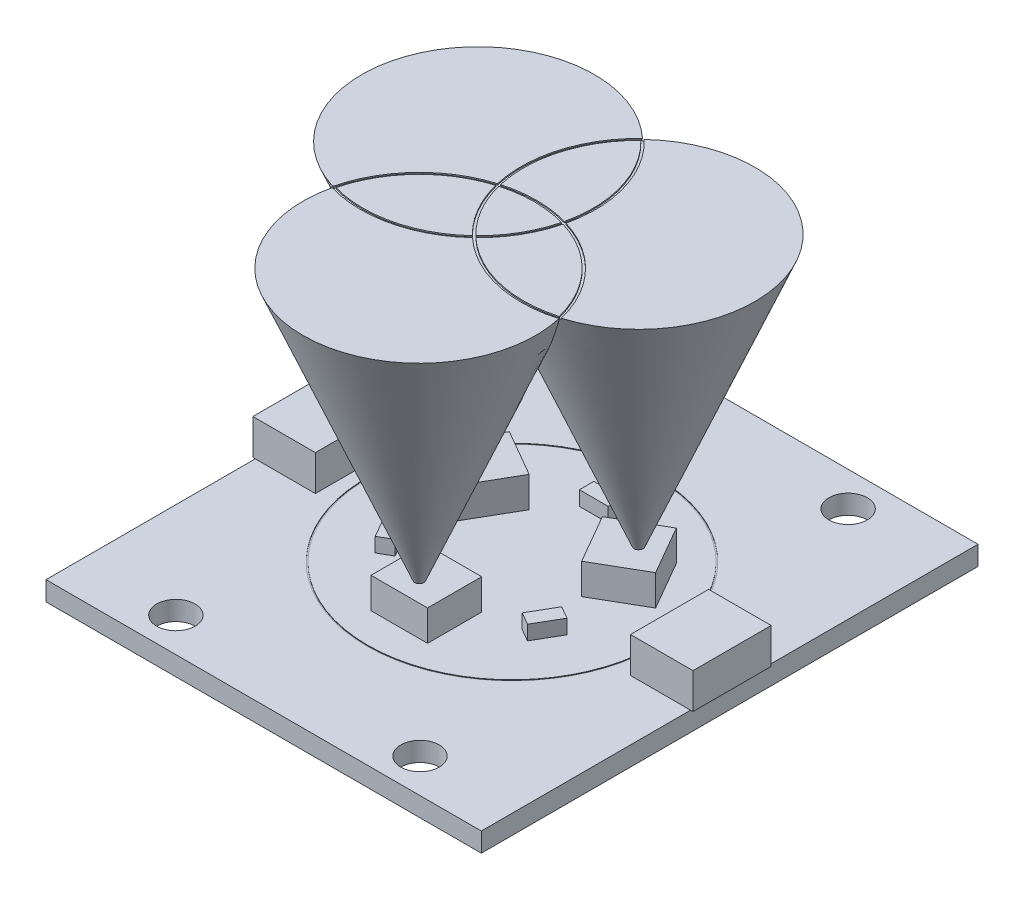
SolidWorks part; units mm, degrees
ref_plane "Front Plane" through (0, 0, 0) normal (0, 0, 1) x (1, 0, 0)
ref_plane "Top Plane" through (0, 0, 0) normal (0, 1, 0) x (1, 0, 0)
ref_plane "Right Plane" through (0, 0, 0) normal (1, 0, 0) x (0, 0, -1)
sketch "Sketch1" plane through (0, 0, 0) normal (0, 1, 0) x (1, 0, 0)
  line L1 (-18.1, -20.65) -> (18.1, -20.65)
  line L2 (-18.1, -20.65) -> (-18.1, 20.65)
  line L3 (-18.1, 20.65) -> (18.1, 20.65)
  line L4 (18.1, -20.65) -> (18.1, 20.65)
  line L5 (-18.1, -20.65) -> (18.1, 20.65) construction
  line L6 (-18.1, 20.65) -> (18.1, -20.65) construction
  line L7 (10.15, -17.8) -> (-10.15, -17.8) construction
  line L8 (10.15, -17.8) -> (10.15, 17.8) construction
  line L9 (10.15, 17.8) -> (-10.15, 17.8) construction
  line L10 (-10.15, -17.8) -> (-10.15, 17.8) construction
  line L11 (10.15, -17.8) -> (-10.15, 17.8) construction
  line L12 (10.15, 17.8) -> (-10.15, -17.8) construction
  circle A0 centre (-10.15, 17.8) radius 1.6
  circle A1 centre (10.15, 17.8) radius 1.6
  circle A2 centre (-10.15, -17.8) radius 1.6
  circle A3 centre (10.15, -17.8) radius 1.6
  point P0 (0, 0)
  point P6 (0, 0)
  dimension "D3" = 3.2
  dimension "D1" = 36.2
  dimension "D2" = 41.3
  dimension "D4" = 20.3
  dimension "D5" = 35.6
extrude "Boss-Extrude1" add sketch "Sketch1" along normal blind 1.6
sketch "Sketch2" plane through (0, 1.6, 0) normal (0, 1, 0) x (1, 0, 0)
  line L0 (-18.1, 0) -> (18.1, 0) construction
  line L2 (18.1, -20.65) -> (18.1, 20.65) construction
  line L3 (-18.1, 20.65) -> (-18.1, -20.65) construction
  line L4 (-18.3, 3.25) -> (-13.1, 3.25)
  line L5 (-18.3, 3.25) -> (-18.3, -3.25)
  line L6 (-18.3, -3.25) -> (-13.1, -3.25)
  line L7 (-13.1, 3.25) -> (-13.1, -3.25)
  line L8 (18.3, 3.25) -> (13.1, 3.25)
  line L9 (18.3, 3.25) -> (18.3, -3.25)
  line L10 (18.3, -3.25) -> (13.1, -3.25)
  line L11 (13.1, 3.25) -> (13.1, -3.25)
  point P14 (13.1, 0)
  point P15 (-13.1, 0)
  dimension "D1" = 6.5
  dimension "D2" = 5.2
  dimension "D3" = 0.2
  dimension "D4" = 0.2
extrude "Boss-Extrude2" add sketch "Sketch2" along normal blind 2.95
sketch "Sketch3" plane through (0, 1.6, 0) normal (0, 1, 0) x (1, 0, 0)
  line L0 (-6.9417, 6.7213) -> (-3.0446, 4.4713)
  line L1 (-6.9417, 6.7213) -> (-9.2917, 2.651)
  line L2 (-3.0446, 4.4713) -> (-5.3946, 0.401)
  line L3 (-9.2917, 2.651) -> (-5.3946, 0.401)
  line L4 (3.0446, 4.4713) -> (6.9417, 6.7213)
  line L5 (3.0446, 4.4713) -> (5.3946, 0.401)
  line L6 (6.9417, 6.7213) -> (9.2917, 2.651)
  line L7 (5.3946, 0.401) -> (9.2917, 2.651)
  line L8 (-2.35, -4.8723) -> (2.35, -4.8723)
  line L9 (-2.35, -4.8723) -> (-2.35, -9.3723)
  line L10 (2.35, -4.8723) -> (2.35, -9.3723)
  line L11 (-2.35, -9.3723) -> (2.35, -9.3723)
  line L12 (0, 0) -> (-6.4952, 3.75) construction
  line L13 (0, 0) -> (6.4952, 3.75) construction
  line L14 (0, 0) -> (0, -7.5) construction
  circle A0 centre (0, 0) radius 7.5 construction
  circle A1 centre (0, 0) radius 12 construction
  point P18 (0, -4.8723)
  point P19 (4.2196, 2.4362)
  point P20 (-4.2196, 2.4362)
  point P21 (-4.9931, 5.5963)
  point P22 (4.9931, 5.5963)
  point P24 (2.35, -7.1223)
  dimension "D3" = 15
  dimension "D4" = 24
  dimension "D1" = 120
  dimension "D2" = 120
  dimension "D5" = 4.7
  dimension "D6" = 4.5
extrude "Boss-Extrude3" add sketch "Sketch3" along normal blind 2.55 contours L1 L3 L2 L0
sketch "Sketch4" plane through (0, 1.6, 0) normal (0, 1, 0) x (1, 0, 0)
  line L0 (0, 0) -> (0, 7.5) construction
  line L1 (0, 0) -> (6.4952, -3.75) construction
  line L2 (0, 0) -> (-6.4952, -3.75) construction
  line L3 (-1.2, 8.0034) -> (1.2, 8.0034)
  line L4 (-1.2, 8.0034) -> (-1.2, 6.8034)
  line L5 (1.2, 8.0034) -> (1.2, 6.8034)
  line L6 (-1.2, 6.8034) -> (1.2, 6.8034)
  line L7 (6.4919, -2.3625) -> (5.2919, -4.4409)
  line L8 (6.4919, -2.3625) -> (7.5311, -2.9625)
  line L9 (5.2919, -4.4409) -> (6.3311, -5.0409)
  line L10 (7.5311, -2.9625) -> (6.3311, -5.0409)
  line L11 (-6.4919, -2.3625) -> (-5.2919, -4.4409)
  line L12 (-6.4919, -2.3625) -> (-7.5311, -2.9625)
  line L13 (-5.2919, -4.4409) -> (-6.3311, -5.0409)
  line L14 (-7.5311, -2.9625) -> (-6.3311, -5.0409)
  circle A0 centre (0, 0) radius 7.5 construction
  point P5 (-7.0115, -2.6625)
  point P17 (7.0115, -2.6625)
  point P20 (5.8919, -3.4017)
  point P21 (-5.8919, -3.4017)
  point P22 (0, 6.8034)
  point P23 (1.2, 7.4034)
  dimension "D1" = 15
  dimension "D2" = 120
  dimension "D3" = 120
  dimension "D4" = 2.4
  dimension "D5" = 1.2
extrude "Boss-Extrude4" add sketch "Sketch4" along normal blind 1.2
sketch "Sketch5" plane through (0, 1.6, 0) normal (0, 1, 0) x (1, 0, 0)
  circle A0 centre (0, 0) radius 12
  circle A1 centre (0, 0) radius 12.1
  dimension "D1" = 0.1
  dimension "D2" = 24
extrude "Cut-Extrude1" cut sketch "Sketch5" against normal blind 0.05
ref_plane "Plane1" through (0, 3.6, 0) normal (0, 1, 0) x (1, 0, 0)
sketch "Sketch6" plane through (0, 3.6, 0) normal (0, 1, 0) x (1, 0, 0)
  line L0 (0, -7.7066) -> (0, 0) construction
  line L1 (0, 0) -> (-6.6741, 3.8533) construction
  line L2 (0, 0) -> (6.6741, 3.8533) construction
  circle A0 centre (-6.6741, 3.8533) radius 0.375
  circle A1 centre (6.6741, 3.8533) radius 0.375
  circle A2 centre (0, -7.7066) radius 0.375
  circle A3 centre (0, 0) radius 7.7066 construction
  dimension "D1" = 0.75
  dimension "D2" = 120
  dimension "D3" = 120
extrude "Cut-Extrude2" cut sketch "Sketch6" along normal through all
ref_plane "Plane2" through (0, 0, 0) normal (1, 0, 0) x (0, 0, -1)
sketch "Sketch7" plane through (0, 0, 0) normal (1, 0, 0) x (0, 0, -1)
  line L0 (-7.3316, 4.15) -> (-8.0816, 4.15) construction
  line L1 (-7.3316, 3.6) -> (-8.0816, 3.6) construction
  line L2 (-7.3316, 4.15) -> (-8.0816, 4.15) construction
  line L3 (-7.3316, 3.6) -> (-8.0816, 3.6) construction
  line L5 (1.9675, 26.6) -> (-7.7066, 26.6)
  line L6 (-7.7066, 26.6) -> (-7.7066, 3.6)
  line L7 (-9.3723, 1.6) -> (-4.8723, 1.6) construction
  line L8 (-7.3316, 4.15) -> (-7.3316, 3.6)
  line L9 (-7.3316, 3.6) -> (-7.7066, 3.6)
  line L10 (-7.3316, 4.15) -> (1.9675, 26.6)
  point P10 (-7.7066, 3.6)
  dimension "D1" = 22.5
  dimension "D2" = 25
revolve "Revolve3" add sketch "Sketch7" angle 360 about L6
pattern_circular "CirPattern2" count 3 over 360 about axis through (0, 0, 0) along (0, 1, 0) of "Revolve3"
sketch "Sketch8" plane through (0, 26.6, 0) normal (0, 1, 0) x (1, 0, 0)
  line L0 (-9.4979, -5.3995) -> (-9.4251, -5.5257)
  line L1 (0.0728, 10.9252) -> (-0.0728, 10.9252)
  line L2 (9.4251, -5.5257) -> (9.4979, -5.3995)
  arc A0 (9.4251, -5.5257) -> (-9.4251, -5.5257) centre (0, -7.7066) ccw construction
  arc A1 (-9.4979, -5.3995) -> (-0.0728, 10.9252) centre (-6.6741, 3.8533) ccw construction
  arc A2 (0.0728, 10.9252) -> (9.4979, -5.3995) centre (6.6741, 3.8533) ccw construction
  arc A3 (0, -3.0111) -> (2.6077, 1.5055) centre (-6.6741, 3.8533) ccw
  arc A4 (-9.402, -5.4282) -> (9.402, -5.4282) centre (0, -7.7066) ccw construction
  arc A5 (9.402, -5.4282) -> (0, 10.8565) centre (6.6741, 3.8533) ccw construction
  arc A6 (0, 10.8565) -> (-9.402, -5.4282) centre (-6.6741, 3.8533) ccw construction
  arc A7 (9.4979, -5.3995) -> (2.847, 1.6437) centre (0, -7.7066) ccw
  arc A8 (-0.0728, 10.9252) -> (-2.847, 1.6437) centre (6.6741, 3.8533) ccw
  arc A9 (-9.4251, -5.5257) -> (0, -3.2874) centre (-6.6741, 3.8533) ccw
  arc A11 (0, 10.7177) -> (-2.6547, 1.7001) centre (6.6741, 3.8533) ccw
  arc A12 (-9.2818, -5.3588) -> (-0.1449, -3.1491) centre (-6.6741, 3.8533) ccw
  circle A13 centre (-6.6741, 3.8533) radius 9.6741 construction
  circle A14 centre (-6.6741, 3.8533) radius 9.7741 construction
  circle A15 centre (0, -7.7066) radius 9.7741 construction
  circle A16 centre (0, -7.7066) radius 9.6741 construction
  arc A17 (0, -3.2874) -> (9.4251, -5.5257) centre (6.6741, 3.8533) ccw
  circle A18 centre (-6.6741, 3.8533) radius 9.5741 construction
  circle A19 centre (6.6741, 3.8533) radius 9.7741 construction
  circle A20 centre (6.6741, 3.8533) radius 9.6741 construction
  circle A21 centre (6.6741, 3.8533) radius 9.5741 construction
  arc A22 (9.2818, -5.3588) -> (2.7997, 1.449) centre (0, -7.7066) ccw
  arc A23 (0.1449, -3.1491) -> (9.2818, -5.3588) centre (6.6741, 3.8533) ccw
  arc A24 (0.1449, -3.1491) -> (2.7997, 1.449) centre (-6.6741, 3.8533) ccw
  arc A25 (-2.847, 1.6437) -> (-9.4979, -5.3995) centre (0, -7.7066) ccw
  arc A26 (-2.7997, 1.449) -> (-0.1449, -3.1491) centre (6.6741, 3.8533) ccw
  arc A27 (-2.7997, 1.449) -> (-9.2818, -5.3588) centre (0, -7.7066) ccw
  arc A28 (-2.6077, 1.5055) -> (0, -3.0111) centre (6.6741, 3.8533) ccw
  arc A29 (2.6547, 1.7001) -> (0, 10.7177) centre (-6.6741, 3.8533) ccw
  arc A30 (2.6547, 1.7001) -> (-2.6547, 1.7001) centre (0, -7.7066) ccw
  arc A31 (2.847, 1.6437) -> (0.0728, 10.9252) centre (-6.6741, 3.8533) ccw
  arc A32 (2.6077, 1.5055) -> (-2.6077, 1.5055) centre (0, -7.7066) ccw
  dimension "D1" = 0.1
  dimension "D2" = 0.1
extrude "Cut-Extrude3" cut sketch "Sketch8" against normal blind 0.1
